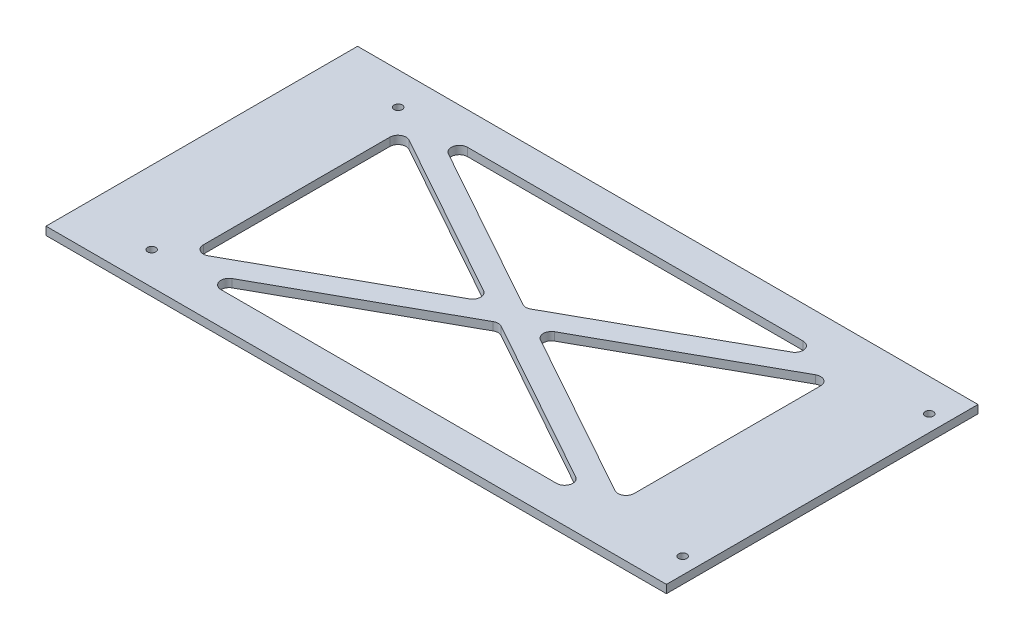
SolidWorks part; units mm, degrees
ref_plane "前视基准面" through (0, 0, 0) normal (0, 0, 1) x (1, 0, 0)
ref_plane "上视基准面" through (0, 0, 0) normal (0, 1, 0) x (1, 0, 0)
ref_plane "右视基准面" through (0, 0, 0) normal (1, 0, 0) x (0, 0, -1)
sketch "草图1" plane through (0, 0, 0) normal (0, 1, 0) x (1, 0, 0)
  line L1 (-1.2102, 35.3016) -> (227.7898, 35.3016)
  line L2 (-1.2102, 35.3016) -> (-1.2102, -79.6984)
  line L3 (-1.2102, -79.6984) -> (227.7898, -79.6984)
  line L4 (227.7898, 35.3016) -> (227.7898, -79.6984)
  line L7 (25.7898, 23.3016) -> (25.7898, -67.6984) construction
  line L8 (221.7898, 23.3016) -> (221.7898, -67.6984) construction
  line L243 (39.7898, 23.3016) -> (192.7898, -61.6984) construction
  line L244 (33.7898, 23.3016) -> (192.7898, 23.3016) construction
  line L245 (33.7898, 23.3016) -> (33.7898, -67.6984) construction
  line L246 (33.7898, -67.6984) -> (192.7898, -67.6984) construction
  line L247 (192.7898, 23.3016) -> (192.7898, -67.6984) construction
  line L248 (33.7898, 17.3016) -> (186.7898, -67.6984) construction
  line L249 (192.7898, 17.3016) -> (39.7898, -67.6984) construction
  line L250 (33.7898, -61.6984) -> (186.7898, 23.3016) construction
  line L251 (49.9102, 17.6792) -> (111.8328, -16.7223)
  line L252 (114.7467, -16.7223) -> (176.6693, 17.6792)
  line L253 (175.2124, 23.3016) -> (51.3671, 23.3016)
  line L254 (192.7898, 12.2031) -> (192.7898, -56.5998)
  line L255 (188.3328, -59.2223) -> (126.4102, -24.8208)
  line L256 (126.4102, -19.5759) -> (188.3328, 14.8256)
  line L257 (114.7467, -27.6744) -> (176.6693, -62.0759)
  line L258 (175.2124, -67.6984) -> (51.3671, -67.6984)
  line L259 (49.9102, -62.0759) -> (111.8328, -27.6744)
  line L260 (100.1693, -19.5759) -> (38.2467, 14.8256)
  line L261 (33.7898, 12.2031) -> (33.7898, -56.5998)
  line L262 (38.2467, -59.2223) -> (100.1693, -24.8208)
  circle A2 centre (25.7898, 23.3016) radius 1.5
  circle A3 centre (25.7898, -67.6984) radius 1.5
  circle A4 centre (221.7898, 23.3016) radius 1.5
  circle A5 centre (221.7898, -67.6984) radius 1.5
  arc A6 (33.7898, 12.2031) -> (38.2467, 14.8256) centre (36.7898, 12.2031) cw
  arc A7 (111.8328, -27.6744) -> (114.7467, -27.6744) centre (113.2898, -30.2969) cw
  arc A8 (126.4102, -24.8208) -> (126.4102, -19.5759) centre (127.8671, -22.1984) cw
  arc A9 (114.7467, -16.7223) -> (111.8328, -16.7223) centre (113.2898, -14.0998) cw
  arc A10 (100.1693, -24.8208) -> (100.1693, -19.5759) centre (98.7124, -22.1984) ccw
  arc A11 (38.2467, -59.2223) -> (33.7898, -56.5998) centre (36.7898, -56.5998) cw
  arc A12 (51.3671, -67.6984) -> (49.9102, -62.0759) centre (51.3671, -64.6984) cw
  arc A13 (175.2124, -67.6984) -> (176.6693, -62.0759) centre (175.2124, -64.6984) ccw
  arc A14 (188.3328, -59.2223) -> (192.7898, -56.5998) centre (189.7898, -56.5998) ccw
  arc A15 (192.7898, 12.2031) -> (188.3328, 14.8256) centre (189.7898, 12.2031) ccw
  arc A16 (176.6693, 17.6792) -> (175.2124, 23.3016) centre (175.2124, 20.3016) ccw
  arc A17 (49.9102, 17.6792) -> (51.3671, 23.3016) centre (51.3671, 20.3016) cw
  point P8 (-1.2102, -22.1984)
  point P9 (25.7898, -22.1984)
  point P14 (221.7898, -22.1984)
  point P15 (227.7898, -22.1984)
  point P16 (113.2898, 39.4338)
  point P19 (113.2898, 35.3016)
  point P34 (0, 0)
  point P35 (0, 0)
  point P37 (0, 0)
  point P38 (0, 0)
  point P39 (0, 0)
  point P40 (0, 0)
  point P41 (113.2898, -17.5317)
  point P42 (0, 0)
  point P47 (113.2898, -26.865)
  point P50 (121.6898, -22.1984)
  point P53 (113.2898, -17.5317)
  point P56 (104.8898, -22.1984)
  dimension "D4" = 27
  dimension "D3" = 91
  dimension "D6" = 91
  dimension "D8" = 6
  dimension "D9" = 6
  dimension "D17" = 3
  dimension "D1" = 229
  dimension "D2" = 35
  dimension "D5" = 6
  dimension "D7" = 35
  dimension "D10" = 6
  dimension "D11" = 6
  dimension "D12" = 115
  dimension "D13" = 6
  dimension "D14" = 6
  dimension "D15" = 6
  dimension "D16" = 6
extrude "凸台-拉伸6" add sketch "草图1" along normal blind 3
